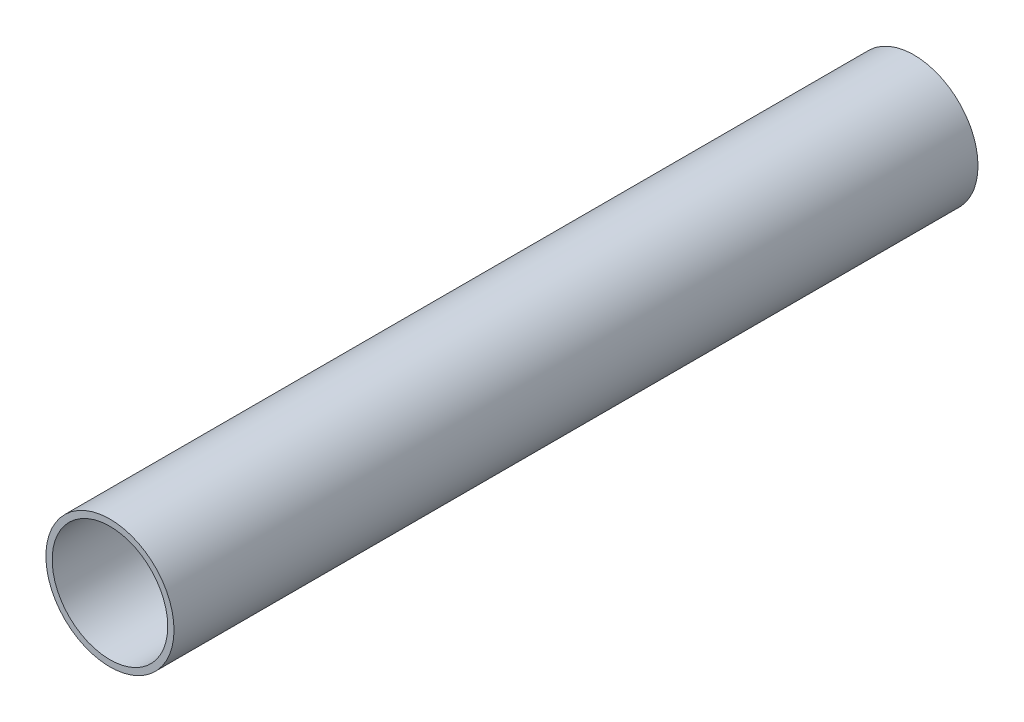
SolidWorks part; units mm, degrees
material "Thornel Mat VMA"
ref_plane "Front Plane" through (0, 0, 0) normal (0, 0, 1) x (1, 0, 0)
ref_plane "Top Plane" through (0, 0, 0) normal (0, 1, 0) x (1, 0, 0)
ref_plane "Right Plane" through (0, 0, 0) normal (1, 0, 0) x (0, 0, -1)
sketch "Sketch1" plane through (0, 0, 0) normal (0, 0, 1) x (1, 0, 0)
  circle A0 centre (0, 0) radius 12.75
  circle A1 centre (0, 0) radius 11.5
  dimension "D1" = 25.5
  dimension "D2" = 23
extrude "Boss-Extrude1" add sketch "Sketch1" along normal blind 160
